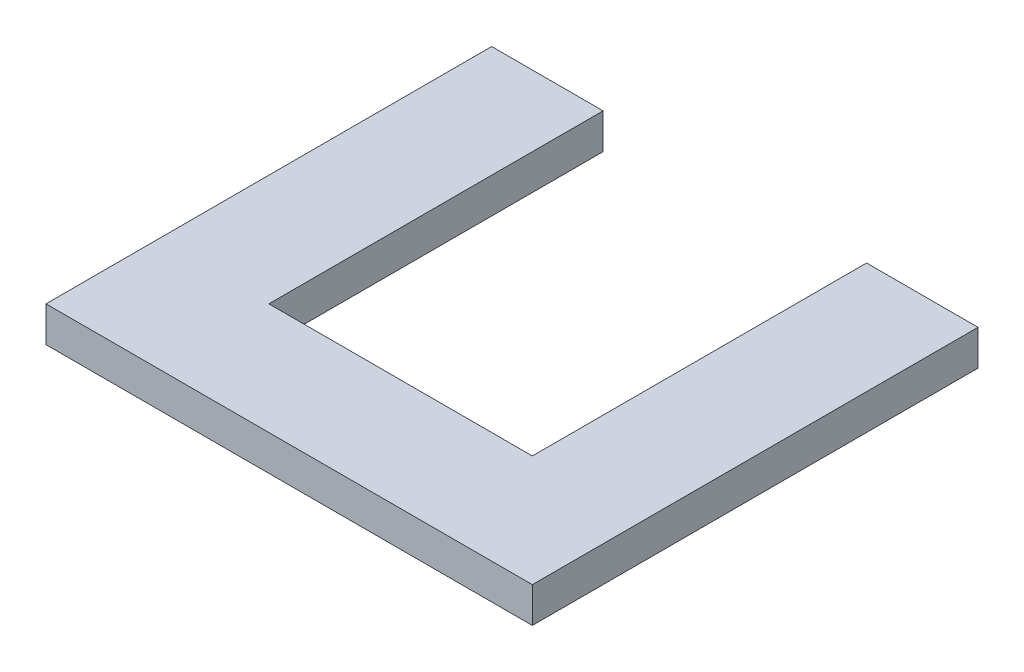
SolidWorks part; units mm, degrees
ref_plane "Front Plane" through (0, 0, 0) normal (0, 0, 1) x (1, 0, 0)
ref_plane "Top Plane" through (0, 0, 0) normal (0, 1, 0) x (1, 0, 0)
ref_plane "Right Plane" through (0, 0, 0) normal (1, 0, 0) x (0, 0, -1)
sketch "Sketch1" plane through (0, 0, 0) normal (0, 1, 0) x (1, 0, 0)
  line L1 (0, 0) -> (87.3, 0)
  line L2 (0, 0) -> (0, 80)
  line L3 (0, 80) -> (87.3, 80)
  line L4 (87.3, 0) -> (87.3, 80)
  line L5 (20, 80) -> (67.3, 80)
  line L6 (20, 80) -> (20, 20)
  line L7 (20, 20) -> (67.3, 20)
  line L8 (67.3, 80) -> (67.3, 20)
  dimension "D1" = 80
  dimension "D2" = 87.3
  dimension "D3" = 20
  dimension "D4" = 47.3
  dimension "D5" = 20
extrude "Boss-Extrude1" add sketch "Sketch1" along normal blind 6.35 contours L3 L8 L7 L6 L2 L1 L4
